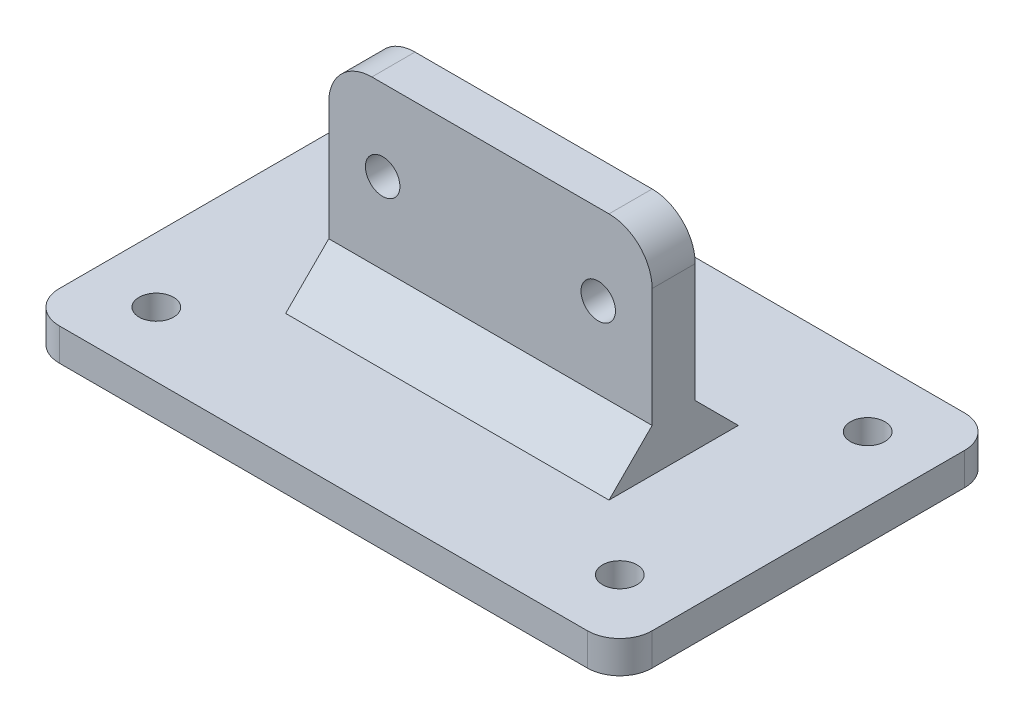
SolidWorks part; units mm, degrees
ref_plane "前视基准面" through (0, 0, 0) normal (0, 0, 1) x (1, 0, 0)
ref_plane "上视基准面" through (0, 0, 0) normal (0, 1, 0) x (1, 0, 0)
ref_plane "右视基准面" through (0, 0, 0) normal (1, 0, 0) x (0, 0, -1)
other "Configuration Table"
sketch "草图1" plane through (0, 0, 0) normal (0, 1, 0) x (1, 0, 0)
  line L1 (0, 0) -> (55, 0)
  line L2 (0, 0) -> (0, 35)
  line L3 (0, 35) -> (55, 35)
  line L4 (55, 0) -> (55, 35)
  dimension "D1" = 55
  dimension "D2" = 35
extrude "凸台-拉伸1" add sketch "草图1" along normal blind 3
sketch "草图2" plane through (0, 3, 0) normal (0, 1, 0) x (1, 0, 0)
  line L0 (49, 29) -> (49, 35) construction
  line L1 (6, 29) -> (49, 29) construction
  line L2 (6, 29) -> (6, 6) construction
  line L3 (6, 6) -> (49, 6) construction
  line L4 (49, 29) -> (49, 6) construction
  line L5 (55, 35) -> (0, 35) construction
  line L6 (49, 6) -> (49, 0) construction
  line L7 (0, 0) -> (55, 0) construction
  line L8 (49, 6) -> (55, 6) construction
  line L9 (55, 0) -> (55, 35) construction
  line L10 (6, 6) -> (0, 6) construction
  line L11 (0, 35) -> (0, 0) construction
  circle A0 centre (6, 29) radius 1.6
  circle A1 centre (49, 29) radius 1.6
  circle A2 centre (49, 6) radius 1.6
  circle A3 centre (6, 6) radius 1.6
  dimension "D1" = 3.2
  dimension "D2" = 3.2
  dimension "D3" = 3.2
  dimension "D4" = 3.2
  dimension "D5" = 23
  dimension "D6" = 43
  dimension "D7" = 180
extrude "切除-拉伸1" cut sketch "草图2" against normal blind 3
fillet "圆角1" radius 3 4 edges at (55, 1.5, -35) (0, 1.5, -35) (0, 1.5, 0) (55, 1.5, 0)
sketch "草图3" plane through (0, 3, 0) normal (0, 1, 0) x (1, 0, 0)
  line L0 (12.5, 19.5) -> (12.5, 35) construction
  line L1 (12.5, 19.5) -> (42.5, 19.5)
  line L2 (12.5, 19.5) -> (12.5, 15.5)
  line L3 (12.5, 15.5) -> (42.5, 15.5)
  line L4 (42.5, 19.5) -> (42.5, 15.5)
  line L5 (52, 35) -> (3, 35) construction
  line L6 (12.5, 15.5) -> (12.5, 0) construction
  line L7 (3, 0) -> (52, 0) construction
  line L8 (12.5, 19.5) -> (0, 19.5) construction
  line L9 (0, 32) -> (0, 3) construction
  line L10 (42.5, 19.5) -> (55, 19.5) construction
  line L11 (55, 3) -> (55, 32) construction
  dimension "D1" = 4
  dimension "D2" = 30
extrude "凸台-拉伸2" add sketch "草图3" along normal blind 19
chamfer "倒角1" distance 4 angle 45 2 edges at (27.5, 3, -15.5) (27.5, 3, -19.5)
sketch "草图4" plane through (0, 0, -19.5) normal (0, 0, -1) x (-1, 0, 0)
  line L1 (-42.5, 7) -> (-12.5, 7) construction
  line L2 (-37.5, 14.5) -> (-42.5, 14.5) construction
  line L5 (-17.5, 14.5) -> (-12.5, 14.5) construction
  line L8 (-12.5, 22) -> (-12.5, 7) construction
  line L9 (-42.5, 22) -> (-42.5, 7) construction
  circle A0 centre (-37.5, 14.5) radius 1.6
  circle A1 centre (-17.5, 14.5) radius 1.6
  dimension "D1" = 3.2
  dimension "D2" = 3.2
  dimension "D3" = 7.5
  dimension "D4" = 7.5
  dimension "D5" = 20
extrude "切除-拉伸2" cut sketch "草图4" against normal blind 19
fillet "圆角3" radius 4 2 edges at (42.5, 22, -17.5) (12.5, 22, -17.5)
